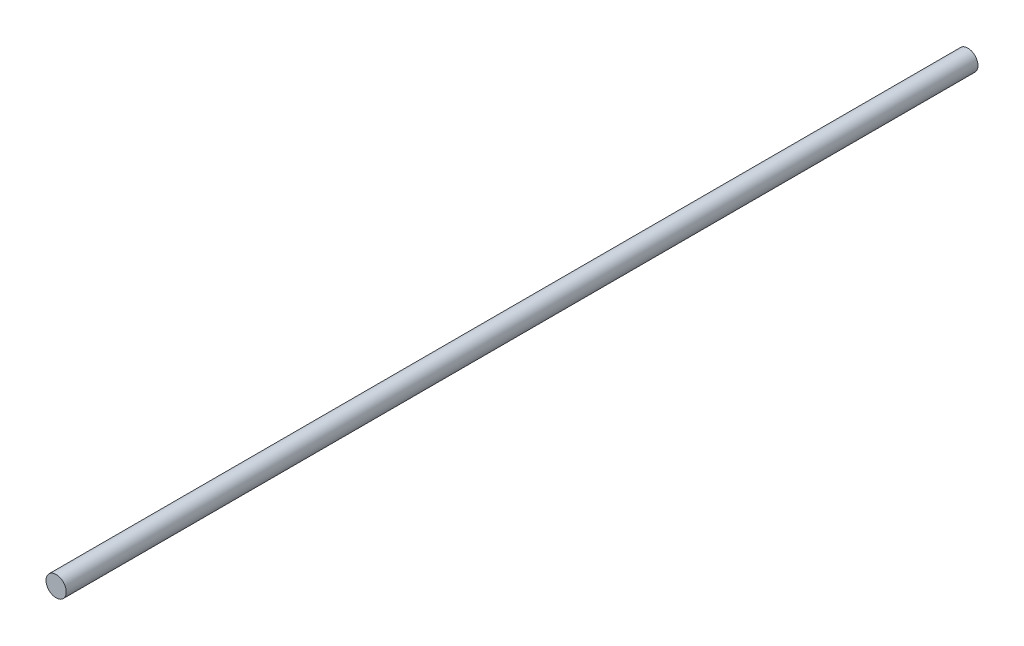
SolidWorks part; units mm, degrees
ref_plane "Front Plane" through (0, 0, 0) normal (0, 0, 1) x (1, 0, 0)
ref_plane "Top Plane" through (0, 0, 0) normal (0, 1, 0) x (1, 0, 0)
ref_plane "Right Plane" through (0, 0, 0) normal (1, 0, 0) x (0, 0, -1)
sketch "Sketch1" plane through (0, 0, 0) normal (0, 0, 1) x (1, 0, 0)
  circle A0 centre (0, 0) radius 5
  dimension "D1" = 10
extrude "Boss-Extrude1" add sketch "Sketch1" along normal blind 450
